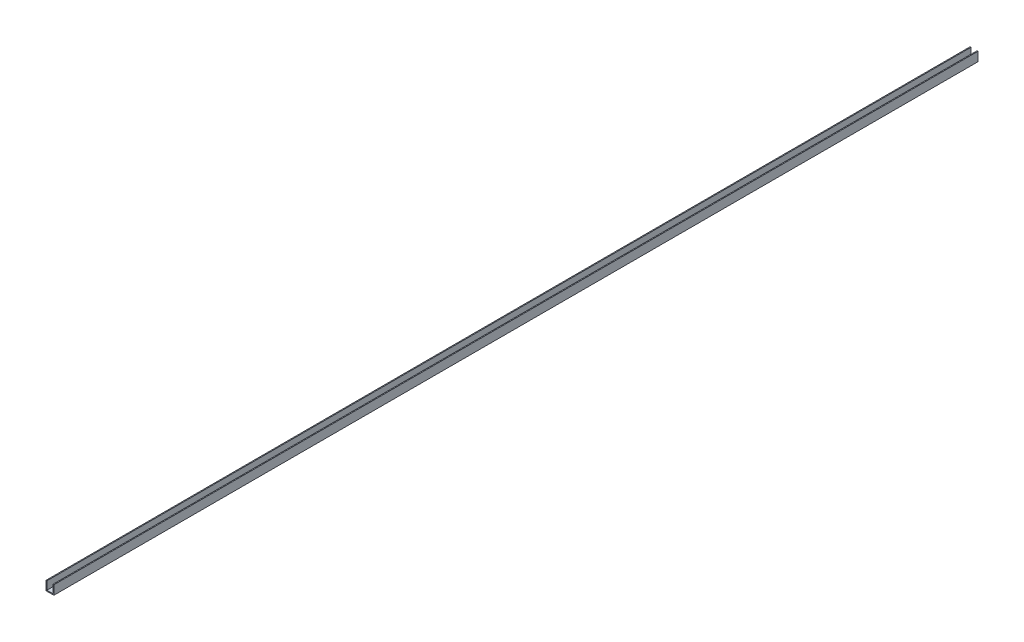
SolidWorks part; units mm, degrees
ref_plane "Front Plane" through (0, 0, 0) normal (0, 0, 1) x (1, 0, 0)
ref_plane "Top Plane" through (0, 0, 0) normal (0, 1, 0) x (1, 0, 0)
ref_plane "Right Plane" through (0, 0, 0) normal (1, 0, 0) x (0, 0, -1)
sketch "Sketch1" plane through (0, 0, 0) normal (0, 0, 1) x (1, 0, 0)
  line L0 (-6.477, 7.493) -> (-6.477, -7.493) construction
  line L1 (-6.477, -7.493) -> (6.477, -7.493) construction
  line L2 (6.477, -7.493) -> (6.477, 7.493) construction
  line L3 (4.953, -5.969) -> (-4.953, -5.969) construction
  line L4 (-4.953, -5.969) -> (-4.953, 7.493) construction
  line L6 (-4.953, 7.493) -> (-6.477, 7.493) construction
  line L7 (0, -7.493) -> (0, 0) construction
  line L8 (6.477, 7.493) -> (4.953, 7.493) construction
  line L9 (4.953, 7.493) -> (4.953, -5.969) construction
  line L10 (0, -5.969) -> (0, -7.493) construction
  point P4 (0, 0)
  dimension "Outside Height" = 14.986
  dimension "Outside Width" = 12.954
  dimension "Wall Thickness" = 1.524
  dimension "D1" = 7.493
  dimension "Inside Height" = 13.462
  dimension "Inside Width" = 9.906
sketch "Sketch2" plane through (0, 0, 0) normal (1, 0, 0) x (0, 0, -1)
  line L0 (762, 7.493) -> (-762, 7.493) construction
  line L1 (0, -5.969) -> (0, 7.493) construction
  point P0 (-747.1029, 7.493)
  point P4 (0, 7.493)
  point P6 (747.1029, 7.493)
  dimension "D1" = 14.8971
  dimension "D2" = 14.8971
  dimension "Length" = 1524
sketch "Sketch3" plane through (0, 0, 0) normal (0, 0, 1) x (1, 0, 0)
  line L6 (-6.477, 7.493) -> (-6.477, -7.493)
  line L7 (-6.477, -7.493) -> (6.477, -7.493)
  line L8 (6.477, -7.493) -> (6.477, 7.493)
  line L9 (6.477, 7.493) -> (4.953, 7.493)
  line L10 (4.953, 7.493) -> (4.953, -5.969)
  line L11 (4.953, -5.969) -> (-4.953, -5.969)
  line L12 (-4.953, -5.969) -> (-4.953, 7.493)
  line L13 (-4.953, 7.493) -> (-6.477, 7.493)
extrude "Boss-Extrude1" add sketch "Sketch3" along normal mid plane 1524
equation "\"D1@Boss-Extrude1\"=\"Length@Sketch2\""
equation "\"D1@Sketch2\" = \"Outside Width@Sketch1\" * 1.15"
equation "\"D2@Sketch2\"=\"D1@Sketch2\""
equation "\"D1@Sketch1\"=\"Outside Height@Sketch1\"/2"
